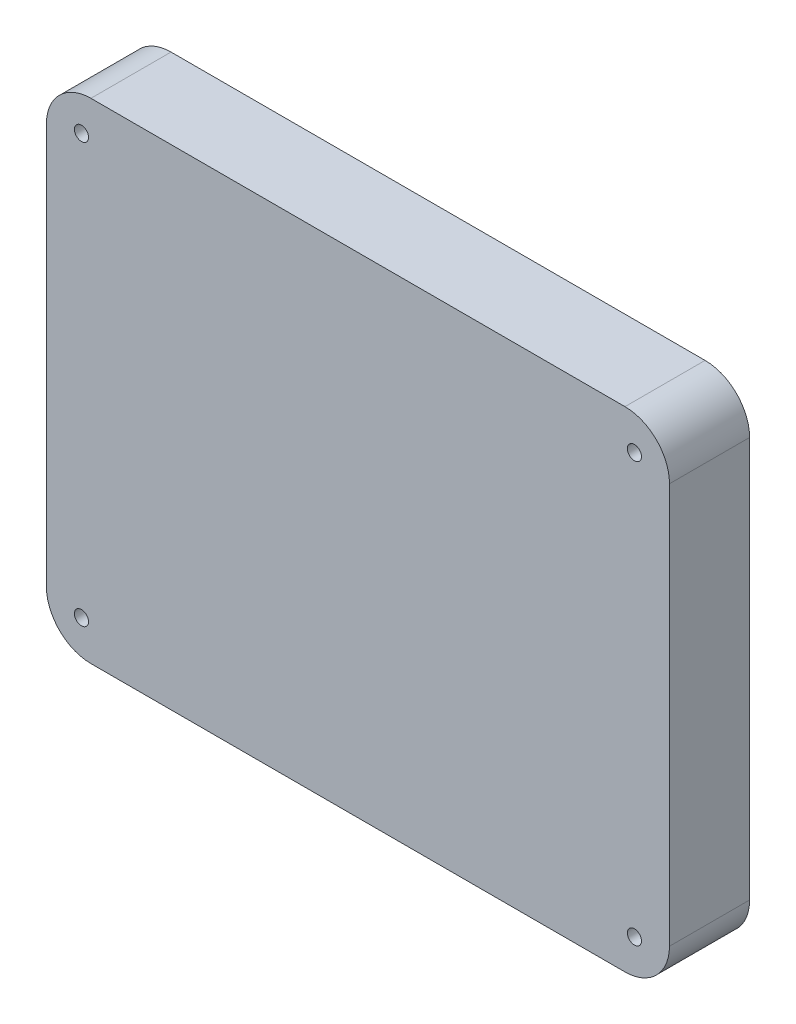
SolidWorks part; units mm, degrees
ref_plane "Front Plane" through (0, 0, 0) normal (0, 0, 1) x (1, 0, 0)
ref_plane "Top Plane" through (0, 0, 0) normal (0, 1, 0) x (1, 0, 0)
ref_plane "Right Plane" through (0, 0, 0) normal (1, 0, 0) x (0, 0, -1)
sketch "Sketch1" plane through (0, 0, 0) normal (0, 0, 1) x (1, 0, 0)
  line L8 (109.9993, 90) -> (-10.0007, 90)
  line L9 (-20.0007, 80) -> (-20.0007, -10)
  line L10 (-10.0007, -20) -> (109.9993, -20)
  line L11 (119.9994, -10) -> (119.9994, 80)
  arc A8 (-10.0007, 90) -> (-20.0007, 80) centre (-10.0007, 80) ccw
  arc A9 (-20.0007, -10) -> (-10.0007, -20) centre (-10.0007, -10) ccw
  arc A10 (109.9993, -20) -> (119.9994, -10) centre (109.9993, -10) ccw
  arc A11 (119.9994, 80) -> (109.9993, 90) centre (109.9994, 80) ccw
extrude "Boss-Extrude1" add sketch "Sketch1" along normal blind 18
sketch "Sketch2" plane through (0, 0, 18) normal (0, 0, 1) x (1, 0, 0)
  circle A0 centre (-12.122, 82.1213) radius 1.5875
  circle A1 centre (-12.122, -12.1213) radius 1.5875
  circle A2 centre (112.1207, 82.1213) radius 1.5875
  circle A3 centre (112.1207, -12.1213) radius 1.5875
  dimension "D1" = 3.175
  dimension "D2" = 3.175
  dimension "D3" = 3.175
  dimension "D4" = 3.175
extrude "Cut-Extrude1" cut sketch "Sketch2" against normal blind 30
